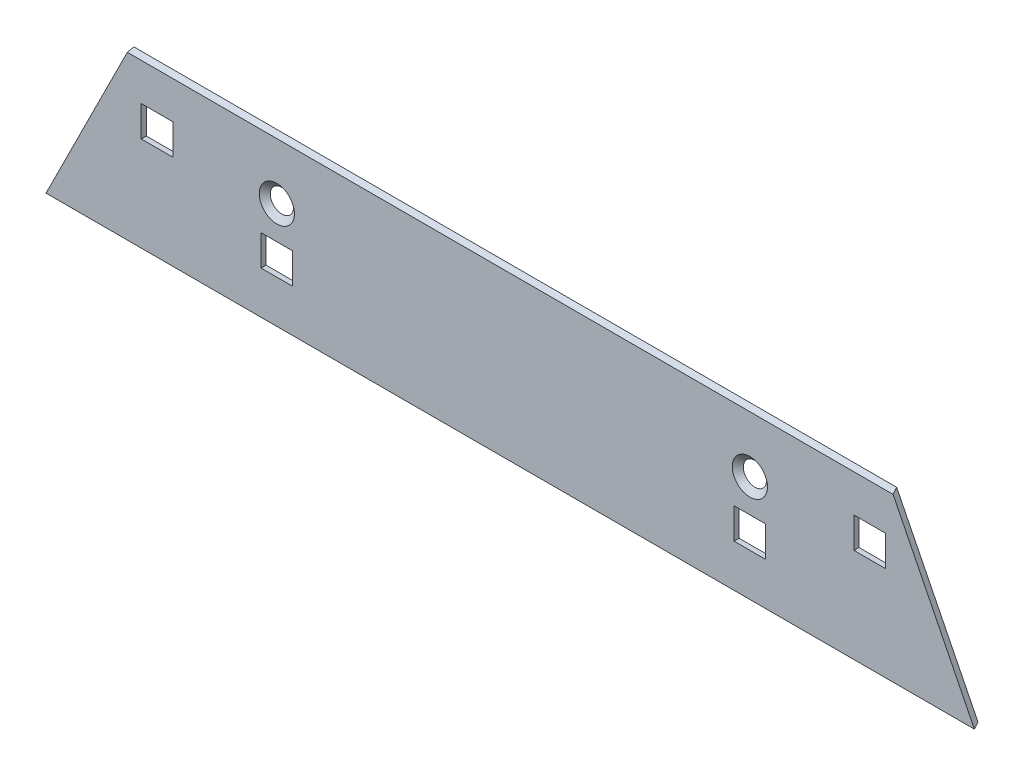
SolidWorks part; units mm, degrees
material "1023 Carbon Steel Sheet (SS)"
ref_plane "Front Plane" through (0, 0, 0) normal (0, 0, 1) x (1, 0, 0)
ref_plane "Top Plane" through (0, 0, 0) normal (0, 1, 0) x (1, 0, 0)
ref_plane "Right Plane" through (0, 0, 0) normal (1, 0, 0) x (0, 0, -1)
sketch "Sketch3" plane through (0, 0, 0) normal (1, 0, 0) x (0, 0, -1)
  line L0 (-0.5715, 31.42) -> (-1.5875, 30.8335)
  line L2 (-0.5715, -1.3309) -> (-0.5715, 31.42)
  line L3 (-1.5875, -1.9175) -> (-0.5715, -1.3309)
  line L4 (-1.5875, -1.9175) -> (-1.5875, 30.8335)
  dimension "D1" = 60
  dimension "D2" = 1.016
  dimension "D3" = 60
  dimension "D4" = 33.3375
extrude "Boss-Extrude2" add sketch "Sketch3" along normal blind 186.944
sketch "Sketch5" plane through (0, 0, 1.5875) normal (0, 0, 1) x (1, 0, 0)
  line L0 (0, -1.9175) -> (16.6723, 31.42)
  line L2 (16.6723, 31.42) -> (0, 31.42)
  line L3 (0, 31.42) -> (0, -1.9175)
  line L4 (186.944, -1.9175) -> (186.944, 31.42)
  line L5 (186.944, 31.42) -> (170.2717, 31.42)
  line L8 (170.2717, 31.42) -> (186.944, -1.9175)
  dimension "D1" = 26.57
  dimension "D2" = 26.57
extrude "Cut-Extrude1" cut sketch "Sketch5" against normal through all
sketch "Sketch6" plane through (0, 0, 1.5875) normal (0, 0, 1) x (1, 0, 0)
  line L0 (25.527, 23.2967) -> (19.177, 23.2967) construction
  line L1 (19.177, 23.2967) -> (19.177, 17.1245) construction
  line L2 (19.177, 17.1245) -> (25.527, 17.1245) construction
  line L3 (25.527, 17.1245) -> (25.527, 23.2967) construction
  line L12 (43.307, 12.8395) -> (43.307, 6.6673) construction
  line L13 (49.657, 12.8395) -> (43.307, 12.8395) construction
  line L14 (43.307, 6.6673) -> (49.657, 6.6673) construction
  line L15 (49.657, 6.6673) -> (49.657, 12.8395) construction
  line L16 (144.907, 12.8395) -> (138.557, 12.8395) construction
  line L17 (144.907, 6.6673) -> (144.907, 12.8395) construction
  line L18 (138.557, 12.8395) -> (138.557, 6.6673) construction
  line L19 (138.557, 6.6673) -> (144.907, 6.6673) construction
  line L20 (162.687, 23.2967) -> (162.687, 17.1245) construction
  line L21 (169.037, 23.2967) -> (162.687, 23.2967) construction
  line L22 (169.037, 17.1245) -> (169.037, 23.2967) construction
  line L23 (162.687, 17.1245) -> (169.037, 17.1245) construction
  line L24 (25.527, 23.2967) -> (19.177, 23.2967)
  line L25 (19.177, 23.2967) -> (19.177, 17.1245)
  line L26 (19.177, 17.1245) -> (25.527, 17.1245)
  line L27 (25.527, 17.1245) -> (25.527, 23.2967)
  line L28 (43.307, 12.8395) -> (43.307, 6.6673)
  line L29 (49.657, 12.8395) -> (43.307, 12.8395)
  line L30 (43.307, 6.6673) -> (49.657, 6.6673)
  line L31 (49.657, 6.6673) -> (49.657, 12.8395)
  line L32 (144.907, 12.8395) -> (138.557, 12.8395)
  line L33 (144.907, 6.6673) -> (144.907, 12.8395)
  line L34 (138.557, 12.8395) -> (138.557, 6.6673)
  line L35 (138.557, 6.6673) -> (144.907, 6.6673)
  line L36 (162.687, 23.2967) -> (162.687, 17.1245)
  line L37 (169.037, 23.2967) -> (162.687, 23.2967)
  line L38 (169.037, 17.1245) -> (169.037, 23.2967)
  line L39 (162.687, 17.1245) -> (169.037, 17.1245)
extrude "Cut-Extrude3" cut sketch "Sketch6" against normal through all
hole_wizard "CSK for #6 Flat Head Machine Screw (100)1" positions "Sketch8" profile "Sketch7" countersink size "#6" standard "ANSI Inch" end condition through all
sketch "Sketch8" plane through (0, 0, 1.5875) normal (0, 0, 1) x (1, 0, 0)
  point P0 (46.482, 19.4867)
  point P3 (141.732, 19.4867)
  point P7 (141.732, 19.4867)
sketch "Sketch7" plane through (46.482, 19.4867, 1.5875) normal (1, 0, 0) x (0, -1, 0)
  line L0 (0, 0) -> (0, 1.016)
  line L1 (0, 1.016) -> (1.8986, 1.016)
  line L2 (1.8986, 1.016) -> (1.8986, 1.38)
  line L3 (1.8986, 1.38) -> (3.5433, 0)
  line L5 (3.5433, 0) -> (0, 0)
  line L6 (-1.8987, 1.38) -> (-3.5433, 0) construction
  line L11 (0, -6.35) -> (0, 107.95) construction
  dimension "Thru Hole Dia." = 3.7973
  dimension "Thru Hole Depth" = 1.016
  dimension "Near C'Sink Dia." = 7.0866
  dimension "Near C'Sink Angle" = 100
